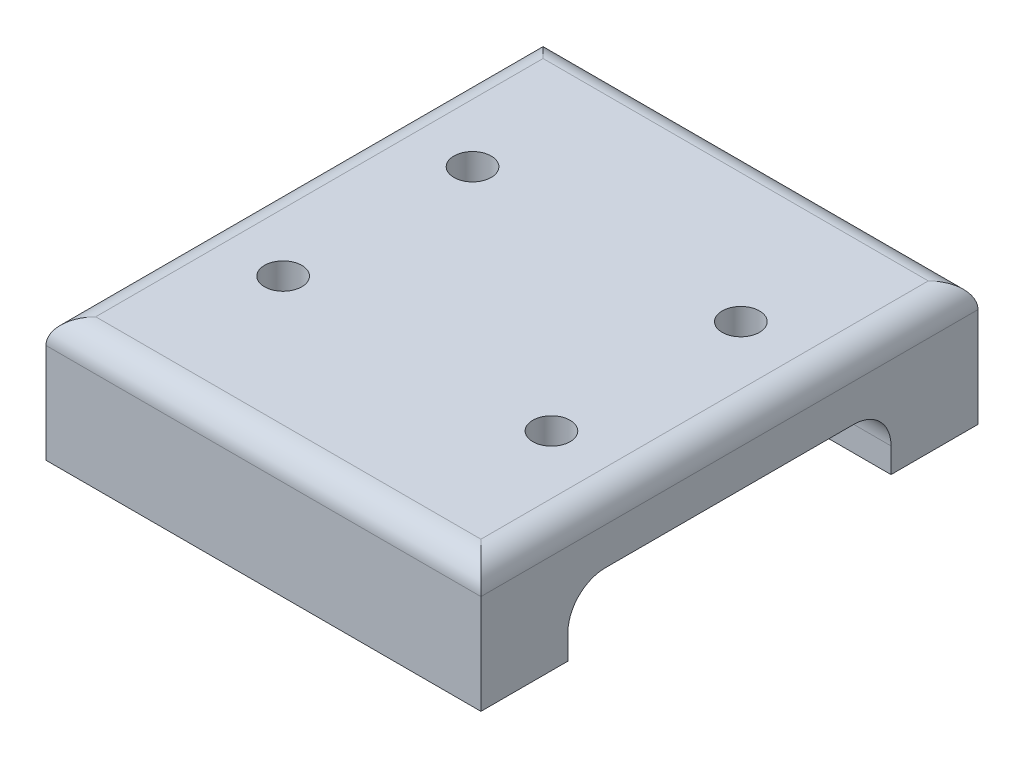
SolidWorks part; units mm, degrees
ref_plane "Front Plane" through (0, 0, 0) normal (0, 0, 1) x (1, 0, 0)
ref_plane "Top Plane" through (0, 0, 0) normal (0, 1, 0) x (1, 0, 0)
ref_plane "Right Plane" through (0, 0, 0) normal (1, 0, 0) x (0, 0, -1)
sketch "Sketch1" plane through (0, 0, 0) normal (0, 1, 0) x (1, 0, 0)
  line L1 (17.5, -20) -> (-17.5, -20)
  line L2 (17.5, -20) -> (17.5, 20)
  line L3 (17.5, 20) -> (-17.5, 20)
  line L4 (-17.5, -20) -> (-17.5, 20)
  line L5 (17.5, -20) -> (-17.5, 20) construction
  line L6 (17.5, 20) -> (-17.5, -20) construction
  point P0 (0, 0)
  dimension "D1" = 35
  dimension "D2" = 40
extrude "Boss-Extrude1" add sketch "Sketch1" along normal blind 5
sketch "Sketch2" plane through (0, 5, 0) normal (0, 1, 0) x (1, 0, 0)
  line L1 (10.795, -7.62) -> (-10.795, -7.62) construction
  line L2 (10.795, -7.62) -> (10.795, 7.62) construction
  line L3 (10.795, 7.62) -> (-10.795, 7.62) construction
  line L4 (-10.795, -7.62) -> (-10.795, 7.62) construction
  line L5 (10.795, -7.62) -> (-10.795, 7.62) construction
  line L6 (10.795, 7.62) -> (-10.795, -7.62) construction
  circle A0 centre (-10.795, 7.62) radius 1.5
  circle A1 centre (10.795, 7.62) radius 1.5
  circle A2 centre (-10.795, -7.62) radius 1.5
  circle A3 centre (10.795, -7.62) radius 1.5
  point P0 (0, 0)
  dimension "D3" = 3
  dimension "D1" = 21.59
  dimension "D2" = 15.24
extrude "Cut-Extrude1" cut sketch "Sketch2" against normal blind 5
sketch "Sketch3" plane through (0, 0, 0) normal (0, -1, 0) x (1, 0, 0)
  line L0 (-10.795, 7.62) -> (10.795, 7.62) construction
  line L1 (0, 7.62) -> (0, 20) construction
  line L2 (-17.5, 20) -> (17.5, 20) construction
  line L4 (17.5, 13) -> (-17.5, 13)
  line L5 (17.5, 13) -> (17.5, 20)
  line L6 (17.5, 20) -> (-17.5, 20)
  line L7 (-17.5, 13) -> (-17.5, 20)
  line L8 (17.5, 13) -> (-17.5, 20) construction
  line L9 (17.5, 20) -> (-17.5, 13) construction
  point P8 (0, 16.5)
  dimension "D1" = 7
extrude "Boss-Extrude2" add sketch "Sketch3" along normal blind 5
sketch "Sketch5" plane through (0, -5, 0) normal (0, -1, 0) x (1, 0, 0)
  line L0 (-17.5, 16.5) -> (17.5, 16.5) construction
  line L1 (-17.5, 20) -> (-17.5, 13) construction
  line L2 (17.5, 13) -> (17.5, 20) construction
  line L3 (0, 16.5) -> (0, 0) construction
  circle A0 centre (-10, 16.5) radius 2
  circle A1 centre (10, 16.5) radius 2
  dimension "D1" = 4
  dimension "D2" = 4
  dimension "D3" = 20
  dimension "D4" = 10
extrude "Cut-Extrude3" cut sketch "Sketch5" against normal blind 8.5
fillet "Fillet2" radius 3 1 edges at (0, 0, 13)
fillet "Fillet3" radius 2 4 edges at (0, 5, 20) (17.5, 5, 0) (0, 5, -20) (-17.5, 5, 0)
mirror "Mirror2" about plane through (0, 0, 0) normal (0, 0, 1) of "Fillet2", "Boss-Extrude2", "Cut-Extrude3"
